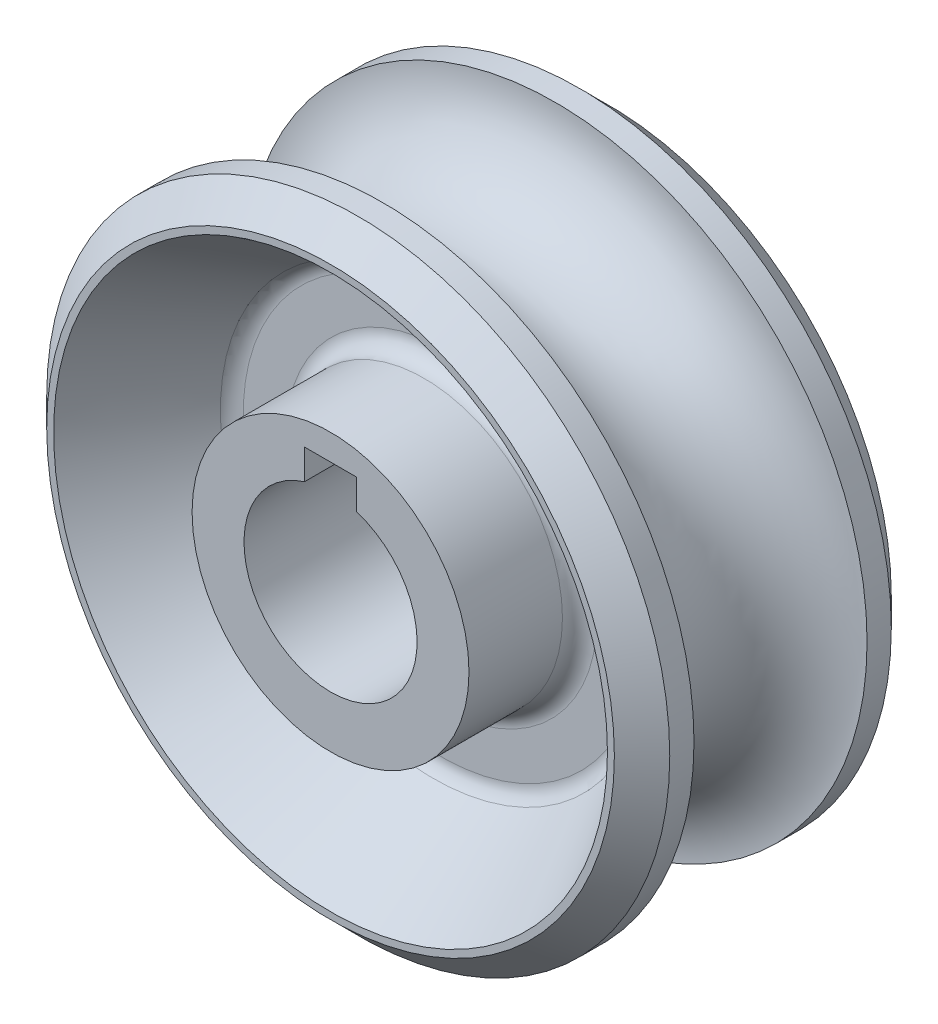
SolidWorks part; units mm, degrees
material "AISI 1020"
ref_plane "Front Plane" through (0, 0, 0) normal (0, 0, 1) x (1, 0, 0)
ref_plane "Top Plane" through (0, 0, 0) normal (0, 1, 0) x (1, 0, 0)
ref_plane "Right Plane" through (0, 0, 0) normal (1, 0, 0) x (0, 0, -1)
sketch "Sketch2" plane through (0, 0, 0) normal (0, 0, 1) x (1, 0, 0)
  circle A0 centre (0, 0) radius 7.9375
  circle A1 centre (0, 0) radius 28.575
  dimension "D1" = 57.15
  dimension "D2" = 15.875
extrude "Boss-Extrude1" add sketch "Sketch2" along normal mid plane 25.4
sketch "Sketch3" plane through (0, 0, 0) normal (1, 0, 0) x (0, 0, -1)
  line L0 (0, 0) -> (15.24, 0) construction
  line L1 (1316.2087, 0) -> (-1316.2087, 0) construction
  line L2 (12.7, 28.575) -> (-12.7, 28.575) construction
  circle A0 centre (0, 28.575) radius 7.9375
  dimension "D1" = 15.875
  dimension "D2" = 15.24
revolve "Cut-Revolve1" cut sketch "Sketch3" angle 360 about L0
sketch "Sketch4" plane through (0, 0, 0) normal (1, 0, 0) x (0, 0, -1)
  line L0 (0, 0) -> (14.4632, 0) construction
  line L1 (1316.2087, 0) -> (-1316.2087, 0) construction
  line L2 (12.7, 25.4) -> (2.54, 19.05)
  line L3 (12.7, -28.575) -> (12.7, 28.575) construction
  line L4 (2.54, 19.05) -> (2.54, 12.7)
  line L5 (2.54, 12.7) -> (12.7, 12.7)
  line L6 (12.7, 12.7) -> (12.7, 25.4)
  line L7 (0, 0) -> (0, 50.8) construction
  line L8 (-12.7, 12.7) -> (-12.7, 25.4)
  line L9 (-2.54, 12.7) -> (-12.7, 12.7)
  line L10 (-2.54, 19.05) -> (-2.54, 12.7)
  line L11 (-12.7, 25.4) -> (-2.54, 19.05)
  dimension "D2" = 25.4
  dimension "D1" = 14.4632
  dimension "D3" = 12.7
  dimension "D4" = 10.16
  dimension "D5" = 6.35
  dimension "D6" = 50.8
revolve "Cut-Revolve2" cut sketch "Sketch4" angle 360 about L0
chamfer "Chamfer1" distance 2.54 angle 45 2 edges at (28.575, 0, -12.7) (28.575, 0, 12.7)
fillet "Fillet1" radius 1.5875 4 edges at (12.7, 0, 2.54) (12.7, 0, -2.54) (19.05, 0, -2.54) (19.05, 0, 2.54)
sketch "Sketch5" plane through (0, 0, 0) normal (0, 0, 1) x (1, 0, 0)
  line L1 (-2.3876, 0) -> (2.3876, 0)
  line L2 (-2.3876, 0) -> (-2.3876, 10.3251)
  line L3 (-2.3876, 10.3251) -> (2.3876, 10.3251)
  line L4 (2.3876, 0) -> (2.3876, 10.3251)
  circle A1 centre (0, 0) radius 7.9375 construction
  point P4 (0, 0)
  dimension "D1" = 4.7752
  dimension "D2" = 2.3876
extrude "Cut-Extrude1" cut sketch "Sketch5" against normal through all both and the other way through all
